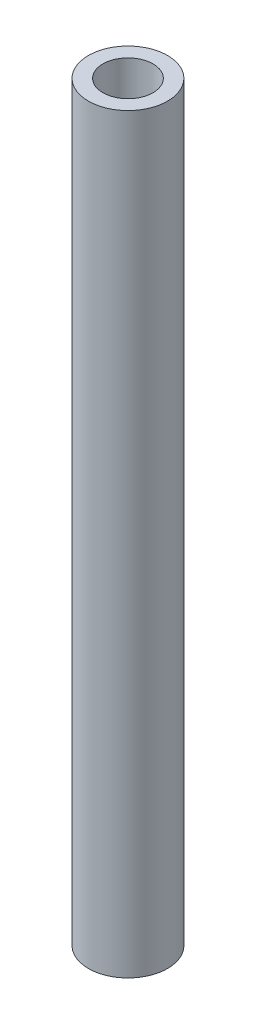
SolidWorks part; units mm, degrees
ref_plane "Front Plane" through (0, 0, 0) normal (0, 0, 1) x (1, 0, 0)
ref_plane "Top Plane" through (0, 0, 0) normal (0, 1, 0) x (1, 0, 0)
ref_plane "Right Plane" through (0, 0, 0) normal (1, 0, 0) x (0, 0, -1)
sketch "Sketch1" plane through (0, 0, 0) normal (0, 1, 0) x (1, 0, 0)
  circle A0 centre (0, 0) radius 3.16
  circle A1 centre (0, 0) radius 2
  dimension "D1" = 6.32
  dimension "D2" = 4
extrude "Boss-Extrude1" add sketch "Sketch1" along normal blind 60
